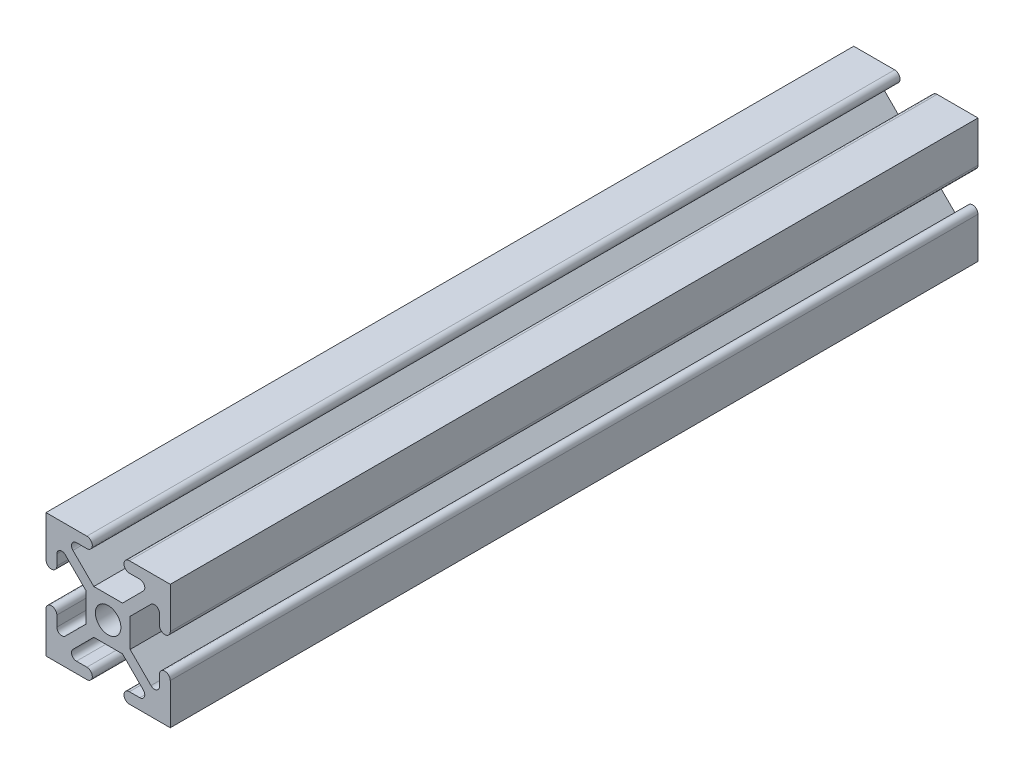
SolidWorks part; units mm, degrees
ref_plane "Front Plane" through (0, 0, 0) normal (0, 0, 1) x (1, 0, 0)
ref_plane "Top Plane" through (0, 0, 0) normal (0, 1, 0) x (1, 0, 0)
ref_plane "Right Plane" through (0, 0, 0) normal (1, 0, 0) x (0, 0, -1)
sketch "Sketch1" plane through (0, 0, 0) normal (0, 0, 1) x (1, 0, 0)
  line L2 (-12.7, -12.7) -> (-4.3434, -12.7)
  line L3 (-4.3434, -10.4902) -> (-6.4748, -10.4902)
  line L4 (-7.1932, -8.7558) -> (-2.9332, -4.4958)
  line L5 (-2.9332, -4.4958) -> (2.9332, -4.4958)
  line L6 (2.9332, -4.4958) -> (7.1932, -8.7558)
  line L7 (6.4748, -10.4902) -> (4.3434, -10.4902)
  line L8 (4.3434, -12.7) -> (12.7, -12.7)
  line L11 (12.7, -12.7) -> (12.7, -4.3434)
  line L12 (10.4902, -4.3434) -> (10.4902, -6.4748)
  line L13 (8.7558, -7.1932) -> (4.4958, -2.9332)
  line L14 (4.4958, -2.9332) -> (4.4958, 2.9332)
  line L15 (4.4958, 2.9332) -> (8.7558, 7.1932)
  line L16 (10.4902, 6.4748) -> (10.4902, 4.3434)
  line L17 (12.7, 4.3434) -> (12.7, 12.7)
  line L20 (12.7, 12.7) -> (4.3434, 12.7)
  line L21 (4.3434, 10.4902) -> (6.4748, 10.4902)
  line L22 (7.1932, 8.7558) -> (2.9332, 4.4958)
  line L23 (2.9332, 4.4958) -> (-2.9332, 4.4958)
  line L24 (-2.9332, 4.4958) -> (-7.1932, 8.7558)
  line L25 (-6.4748, 10.4902) -> (-4.3434, 10.4902)
  line L26 (-4.3434, 12.7) -> (-12.7, 12.7)
  line L29 (-12.7, 12.7) -> (-12.7, 4.3434)
  line L30 (-10.4902, 4.3434) -> (-10.4902, 6.4748)
  line L31 (-8.7558, 7.1932) -> (-4.4958, 2.9332)
  line L32 (-4.4958, 2.9332) -> (-4.4958, -2.9332)
  line L33 (-4.4958, -2.9332) -> (-8.7558, -7.1932)
  line L34 (-10.4902, -6.4748) -> (-10.4902, -4.3434)
  line L35 (-12.7, -4.3434) -> (-12.7, -12.7)
  circle A0 centre (0, 0) radius 2.6035
  arc A6 (-4.3434, -12.7) -> (-4.3434, -10.4902) centre (-4.3434, -11.5951) ccw
  arc A7 (-6.4748, -10.4902) -> (-7.1932, -8.7558) centre (-6.4748, -9.4742) cw
  arc A10 (7.1932, -8.7558) -> (6.4748, -10.4902) centre (6.4748, -9.4742) cw
  arc A11 (4.3434, -10.4902) -> (4.3434, -12.7) centre (4.3434, -11.5951) ccw
  arc A17 (12.7, -4.3434) -> (10.4902, -4.3434) centre (11.5951, -4.3434) ccw
  arc A18 (10.4902, -6.4748) -> (8.7558, -7.1932) centre (9.4742, -6.4748) cw
  arc A21 (8.7558, 7.1932) -> (10.4902, 6.4748) centre (9.4742, 6.4748) cw
  arc A22 (10.4902, 4.3434) -> (12.7, 4.3434) centre (11.5951, 4.3434) ccw
  arc A28 (4.3434, 12.7) -> (4.3434, 10.4902) centre (4.3434, 11.5951) ccw
  arc A29 (6.4748, 10.4902) -> (7.1932, 8.7558) centre (6.4748, 9.4742) cw
  arc A32 (-7.1932, 8.7558) -> (-6.4748, 10.4902) centre (-6.4748, 9.4742) cw
  arc A33 (-4.3434, 10.4902) -> (-4.3434, 12.7) centre (-4.3434, 11.5951) ccw
  arc A39 (-12.7, 4.3434) -> (-10.4902, 4.3434) centre (-11.5951, 4.3434) ccw
  arc A40 (-10.4902, 6.4748) -> (-8.7558, 7.1932) centre (-9.4742, 6.4748) cw
  arc A43 (-8.7558, -7.1932) -> (-10.4902, -6.4748) centre (-9.4742, -6.4748) cw
  arc A44 (-10.4902, -4.3434) -> (-12.7, -4.3434) centre (-11.5951, -4.3434) ccw
  point P101 (-4.4958, 0)
  point P102 (0, 4.4958)
  point P103 (4.4958, 0)
  point P127 (0, -4.4958)
extrude "Boss-Extrude1" add sketch "Sketch1" against normal blind 165.1
